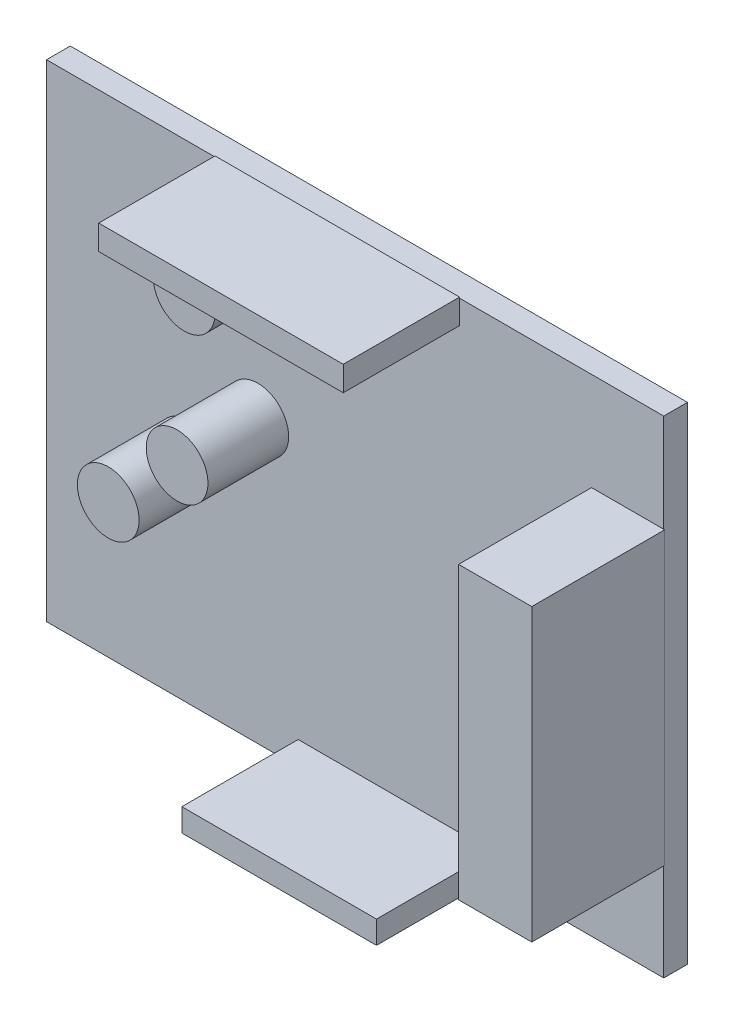
SolidWorks part; units mm, degrees
ref_plane "Front Plane" through (0, 0, 0) normal (0, 0, 1) x (1, 0, 0)
ref_plane "Top Plane" through (0, 0, 0) normal (0, 1, 0) x (1, 0, 0)
ref_plane "Right Plane" through (0, 0, 0) normal (1, 0, 0) x (0, 0, -1)
sketch "Sketch1" plane through (0, 0, 0) normal (0, 0, 1) x (1, 0, 0)
  circle A0 centre (-17.5, -3) radius 3.25
extrude "Boss-Extrude1" add sketch "Sketch1" along normal blind 8.5
sketch "Sketch3" plane through (0, 0, 0) normal (0, 0, 1) x (1, 0, 0)
  line L1 (32.5, -25.625) -> (-32.5, -25.625)
  line L2 (32.5, -25.625) -> (32.5, 25.625)
  line L3 (32.5, 25.625) -> (-32.5, 25.625)
  line L4 (-32.5, -25.625) -> (-32.5, 25.625)
  line L5 (32.5, -25.625) -> (-32.5, 25.625) construction
  line L6 (32.5, 25.625) -> (-32.5, -25.625) construction
  point P0 (0, 0)
extrude "Boss-Extrude2" add sketch "Sketch3" against normal blind 2.5
sketch "Sketch4" plane through (0, 0, 0) normal (0, 0, 1) x (1, 0, 0)
  line L1 (32.5, -15.3) -> (24.9, -15.3)
  line L2 (32.5, -15.3) -> (32.5, 15.3)
  line L3 (32.5, 15.3) -> (24.9, 15.3)
  line L4 (24.9, -15.3) -> (24.9, 15.3)
  line L5 (32.5, -15.3) -> (24.9, 15.3) construction
  line L6 (32.5, 15.3) -> (24.9, -15.3) construction
  point P0 (30.5, 0)
extrude "Boss-Extrude3" add sketch "Sketch4" along normal blind 14
sketch "Sketch5" plane through (0, 0, 0) normal (0, 0, 1) x (1, 0, 0)
  circle A0 centre (-10.25, 4) radius 3.25
extrude "Boss-Extrude4" add sketch "Sketch5" along normal blind 8.5
sketch "Sketch6" plane through (0, 0, 0) normal (0, 0, 1) x (1, 0, 0)
  line L0 (32.5, 25.625) -> (-32.5, 25.625) construction
  line L1 (-14.75, 25.625) -> (11, 25.625)
  line L2 (-14.75, 25.625) -> (-14.75, 23.125)
  line L3 (-14.75, 23.125) -> (11, 23.125)
  line L4 (11, 25.625) -> (11, 23.125)
extrude "Boss-Extrude5" add sketch "Sketch6" along normal blind 12.25
sketch "Sketch8" plane through (0, 0, 0) normal (0, 0, 1) x (1, 0, 0)
  circle A0 centre (-9.5, 19.87) radius 3.25
extrude "Boss-Extrude9" add sketch "Sketch8" along normal blind 8.5 contours A0
sketch "Sketch9" plane through (0, 0, 0) normal (0, 0, 1) x (1, 0, 0)
  line L0 (-32.5, -25.625) -> (32.5, -25.625) construction
  line L1 (-6, -23.125) -> (14.5, -23.125)
  line L2 (-6, -23.125) -> (-6, -25.625)
  line L3 (-6, -25.625) -> (14.5, -25.625)
  line L4 (14.5, -23.125) -> (14.5, -25.625)
extrude "Boss-Extrude10" add sketch "Sketch9" along normal blind 12.25
sketch "Sketch10" plane through (0, -25.625, 0) normal (0, -1, 0) x (1, 0, 0)
  line L1 (-6, 12.25) -> (14.5, 12.25)
  line L2 (-6, 12.25) -> (-6, 0)
  line L3 (-6, 0) -> (14.5, 0)
  line L4 (14.5, 12.25) -> (14.5, 0)
extrude "Cut-Extrude1" cut sketch "Sketch10" against normal blind 0.1
sketch "Sketch12" plane through (0, 25.625, 0) normal (0, 1, 0) x (1, 0, 0)
  line L1 (11, -12.25) -> (-14.75, -12.25)
  line L2 (11, -12.25) -> (11, 0)
  line L3 (11, 0) -> (-14.75, 0)
  line L4 (-14.75, -12.25) -> (-14.75, 0)
extrude "Boss-Extrude11" add sketch "Sketch12" along normal blind 0.1
sketch "Sketch14" plane through (32.5, 0, 0) normal (1, 0, 0) x (0, 0, -1)
  line L1 (-14, 15.3) -> (0, 15.3)
  line L2 (-14, 15.3) -> (-14, -15.3)
  line L3 (-14, -15.3) -> (0, -15.3)
  line L4 (0, 15.3) -> (0, -15.3)
extrude "Boss-Extrude12" add sketch "Sketch14" along normal blind 0.1
